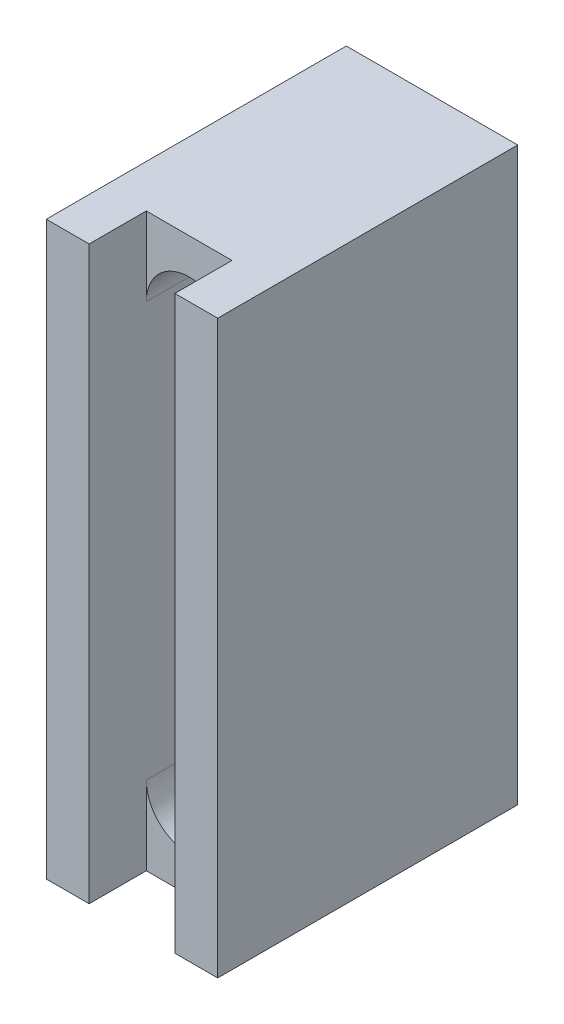
SolidWorks part; units mm, degrees
ref_plane "Plan de face" through (0, 0, 0) normal (0, 0, 1) x (1, 0, 0)
ref_plane "Plan de dessus" through (0, 0, 0) normal (0, 1, 0) x (1, 0, 0)
ref_plane "Plan de droite" through (0, 0, 0) normal (1, 0, 0) x (0, 0, -1)
sketch "Esquisse1" plane through (0, 0, 0) normal (0, 0, 1) x (1, 0, 0)
  line L1 (-6, 20) -> (6, 20)
  line L2 (-6, 20) -> (-6, -20)
  line L3 (-6, -20) -> (6, -20)
  line L4 (6, 20) -> (6, -20)
  dimension "D1" = 12
  dimension "D2" = 40
  dimension "D3" = 20
  dimension "D4" = 6
extrude "Extrusion1" add sketch "Esquisse1" along normal blind 17
sketch "Esquisse2" plane through (0, 0, 17) normal (0, 0, 1) x (1, 0, 0)
  line L0 (-3, 14.5) -> (-3, -14.5)
  line L1 (-6, -20) -> (6, -20) construction
  line L2 (3, -14.5) -> (3, 14.5)
  line L3 (-6, 20) -> (-6, -20) construction
  line L4 (6, -20) -> (6, 20) construction
  arc A0 (-3, -14.5) -> (3, -14.5) centre (0, -14.5) ccw
  arc A1 (-3, 14.5) -> (3, 14.5) centre (0, 14.5) cw
  dimension "D1" = 29
  dimension "D2" = 5.5
  dimension "D3" = 3
  dimension "D4" = 3
extrude "Extrusion2" cut sketch "Esquisse2" against normal blind 12
sketch "Esquisse3" plane through (0, 0, 5) normal (0, 0, 1) x (1, 0, 0)
  line L0 (-3, 1.5) -> (3, 1.5)
  line L1 (-3, 14.5) -> (-3, -14.5) construction
  line L2 (3, -14.5) -> (3, 14.5) construction
  line L3 (3, 1.5) -> (3, -1.5)
  line L4 (3, -1.5) -> (-3, -1.5)
  line L5 (-3, -1.5) -> (-3, 1.5)
  arc A0 (3, 14.5) -> (-3, 14.5) centre (0, 14.5) ccw construction
  arc A1 (-3, -14.5) -> (3, -14.5) centre (0, -14.5) ccw construction
  dimension "D1" = 13
  dimension "D2" = 13
extrude "Extrusion3" cut sketch "Esquisse3" against normal through all
sketch "Esquisse4" plane through (0, 0, 17) normal (0, 0, 1) x (1, 0, 0)
  line L0 (-3, 14.5) -> (-3, -14.5) construction
  line L1 (0, 12.9016) -> (0, -10.386) construction
  line L2 (-6, -20) -> (6, -20) construction
  line L3 (3, 20) -> (6, 20)
  line L4 (6, 20) -> (-6, 20) construction
  line L5 (3, -20) -> (3, 20)
  line L6 (-6, 20) -> (-6, -20)
  line L7 (-6, -20) -> (-3, -20)
  line L8 (-3, -20) -> (-3, 20)
  line L9 (-3, 20) -> (-6, 20)
  line L10 (6, -20) -> (3, -20)
  line L11 (6, 20) -> (6, -20)
extrude "Extrusion4" add sketch "Esquisse4" along normal blind 4
